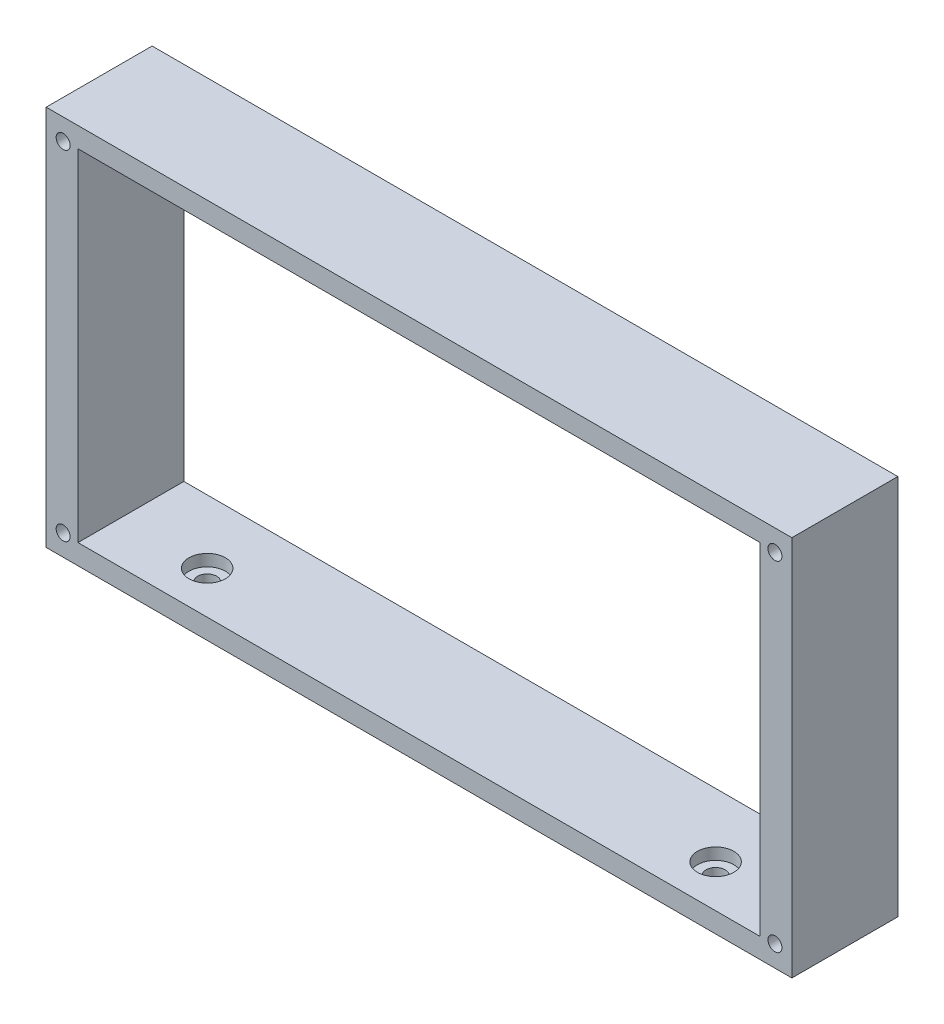
SolidWorks part; units mm, degrees
ref_plane "Front Plane" through (0, 0, 0) normal (0, 0, 1) x (1, 0, 0)
ref_plane "Top Plane" through (0, 0, 0) normal (0, 1, 0) x (1, 0, 0)
ref_plane "Right Plane" through (0, 0, 0) normal (1, 0, 0) x (0, 0, -1)
sketch "Sketch5" plane through (0, 0, 0) normal (0, 0, 1) x (1, 0, 0)
  line L1 (-80.5, -40.25) -> (80.5, -40.25)
  line L2 (-80.5, -40.25) -> (-80.5, 40.25)
  line L3 (-80.5, 40.25) -> (80.5, 40.25)
  line L4 (80.5, -40.25) -> (80.5, 40.25)
  line L5 (-80.5, -40.25) -> (80.5, 40.25) construction
  line L6 (-80.5, 40.25) -> (80.5, -40.25) construction
  line L7 (-88, -45) -> (88, -45)
  line L8 (-88, -45) -> (-88, 45)
  line L9 (-88, 45) -> (88, 45)
  line L10 (88, -45) -> (88, 45)
  line L11 (-88, -45) -> (88, 45) construction
  line L12 (-88, 45) -> (88, -45) construction
  point P0 (0, 0)
  point P6 (0, 0)
  dimension "D1" = 161
  dimension "D2" = 80.5
  dimension "D3" = 176
  dimension "D4" = 90
extrude "Boss-Extrude2" add sketch "Sketch5" along normal blind 25
hole_wizard "M4x0.7 Tapped Hole1" positions "Sketch6" profile "Sketch7" tap size "M4x0.7" standard "ANSI Metric" end condition through all
sketch "Sketch6" plane through (0, 0, 0) normal (0, 0, -1) x (-1, 0, 0)
  line L1 (-84, -40) -> (84, -40)
  line L2 (-84, -40) -> (-84, 40)
  line L3 (-84, 40) -> (84, 40)
  line L4 (84, -40) -> (84, 40)
  line L5 (-84, -40) -> (84, 40) construction
  line L6 (-84, 40) -> (84, -40) construction
  point P1 (0, 0)
  point P2 (84, 40)
  point P115 (-84, -40)
  point P116 (-84, 40)
  point P117 (84, -40)
  dimension "D1" = 168
  dimension "D2" = 80
sketch "Sketch7" plane through (0, 0, 0) normal (1, 0, 0) x (0, 1, 0)
  line L0 (0, 0) -> (0, 25)
  line L1 (0, 25) -> (1.65, 25)
  line L2 (1.65, 25) -> (1.65, 0)
  line L5 (1.65, 0) -> (0, 0)
  line L11 (0, -6.35) -> (0, 107.95) construction
  dimension "Thru Tap Drill Dia." = 3.3
  dimension "Thru Tap Drill Depth" = 25
cosmetic thread "Hole Thread1" parameters "D2"=4
cosmetic thread "Hole Thread2" parameters "D2"=4
cosmetic thread "Hole Thread3" parameters "D2"=4
cosmetic thread "Hole Thread4" parameters "D2"=4
hole_wizard "CBORE for M4 SBHCS1" positions "Sketch8" profile "Sketch10" counterbore size "M4" standard "ANSI Metric"
sketch "Sketch8" plane through (0, -40.25, 0) normal (0, 1, 0) x (1, 0, 0)
  line L0 (-60, -15) -> (60, -15)
  line L2 (-88, -25) -> (88, -25) construction
  point P1 (-60, -15)
  point P2 (60, -15)
  point P9 (0, -15)
  dimension "D1" = 120
  dimension "D2" = 10
sketch "Sketch10" plane through (-60, -40.25, 15) normal (1, 0, 0) x (0, 0, 1)
  line L0 (0, 0) -> (0, 4.75)
  line L1 (0, 4.75) -> (2.25, 4.75)
  line L3 (2.25, 4.75) -> (2.25, 2.75)
  line L4 (2.25, 2.75) -> (4.3, 2.75)
  line L5 (4.3, 2.75) -> (4.3, 0)
  line L7 (4.3, 0) -> (0, 0)
  line L11 (0, -6.35) -> (0, 107.95) construction
  dimension "Thru Hole Dia." = 4.5
  dimension "Thru Hole Depth" = 4.75
  dimension "C'Bore Dia." = 8.6
  dimension "C'Bore Depth" = 2.75
hole_wizard "M4x0.7 Tapped Hole2" positions "Sketch11" profile "Sketch12" tap size "M4x0.7" standard "ANSI Metric"
sketch "Sketch11" plane through (0, 0, 0) normal (0, 0, -1) x (-1, 0, 0)
  line L1 (-10, -42.5) -> (10, -42.5)
  line L2 (-10, -42.5) -> (-10, 42.5)
  line L3 (-10, 42.5) -> (10, 42.5)
  line L4 (10, -42.5) -> (10, 42.5)
  line L5 (-10, -42.5) -> (10, 42.5) construction
  line L6 (-10, 42.5) -> (10, -42.5) construction
  line L7 (-88, 45) -> (88, 45) construction
  point P0 (0, 0)
  point P1 (10, 42.5)
  point P48 (-10, -42.5)
  point P49 (-10, 42.5)
  point P50 (10, -42.5)
  dimension "D1" = 20
  dimension "D2" = 2.5
sketch "Sketch12" plane through (0, 0, 0) normal (1, 0, 0) x (0, 1, 0)
  line L0 (0, 0) -> (0, 5.9914)
  line L1 (0, 5.9914) -> (1.65, 5)
  line L2 (1.65, 5) -> (1.65, 0)
  line L5 (1.65, 0) -> (0, 0)
  line L10 (0, 5.9914) -> (-1.65, 5) construction
  line L11 (0, -6.35) -> (0, 107.95) construction
  dimension "Tap Drill Dia." = 3.3
  dimension "Tap Drill Depth" = 5
  dimension "Drill Angle" = 118
cosmetic thread "Hole Thread5" parameters "D1"=25, "D2"=4
cosmetic thread "Hole Thread6" parameters "D1"=25, "D2"=4
cosmetic thread "Hole Thread7" parameters "D1"=25, "D2"=4
cosmetic thread "Hole Thread8" parameters "D1"=25, "D2"=4
